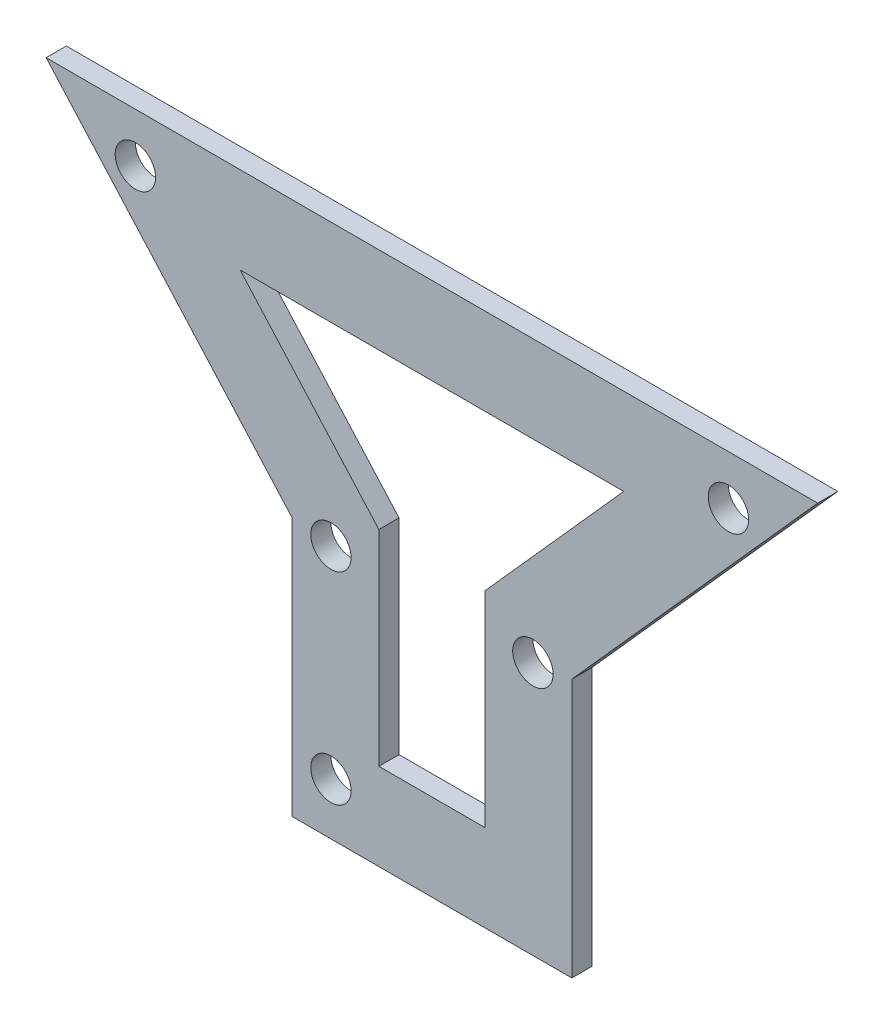
SolidWorks part; units mm, degrees
ref_plane "Спереди" through (0, 0, 0) normal (0, 0, 1) x (1, 0, 0)
ref_plane "Сверху" through (0, 0, 0) normal (0, 1, 0) x (1, 0, 0)
ref_plane "Справа" through (0, 0, 0) normal (1, 0, 0) x (0, 0, -1)
sketch "Эскиз5" plane through (0, 0, 0) normal (0, 0, 1) x (1, 0, 0)
  line L0 (0, -125.6018) -> (0, 84.5398) construction
  line L1 (69.2703, 2.5328) -> (69.2703, -125.6018)
  line L2 (69.2703, 2.5328) -> (190.9954, 138.8843)
  line L3 (190.9954, 138.8843) -> (-190.9954, 138.8843)
  line L4 (69.2703, -125.6018) -> (-69.2703, -125.6018)
  line L5 (-26.2703, -82.6018) -> (26.2703, -82.6018)
  line L6 (26.2703, -82.6018) -> (26.2703, 18.9341)
  line L7 (26.2703, 18.9341) -> (94.9661, 95.8843)
  line L8 (94.9661, 95.8843) -> (-94.9661, 95.8843)
  line L9 (-26.2703, 18.9341) -> (-94.9661, 95.8843)
  line L10 (-26.2703, -82.6018) -> (-26.2703, 18.9341)
  line L11 (-69.2703, 2.5328) -> (-190.9954, 138.8843)
  line L12 (-69.2703, 2.5328) -> (-69.2703, -125.6018)
  circle A0 centre (136.7614, 111.3834) radius 10 construction
  circle A1 centre (50, -10.9786) radius 10 construction
  circle A2 centre (50, -110.9786) radius 10 construction
  circle A3 centre (-50, -110.9786) radius 10 construction
  circle A4 centre (-50, -10.9786) radius 10 construction
  circle A5 centre (-136.7614, 111.3834) radius 10 construction
  point P33 (0, 95.8843)
  point P35 (0, -82.6018)
  point P37 (0, 138.8843)
  dimension "D1" = 20
  dimension "D5" = 43
  dimension "D2" = 50
  dimension "D3" = 100
  dimension "D4" = 150
  dimension "D6" = 43
  dimension "D7" = 43
  dimension "D8" = 43
extrude "Бобышка-Вытянуть2" add sketch "Эскиз5" along normal blind 10 contours L4 L12 L11 L3 L2 L1 | L8 L9 L10 L5 L6 L7
sketch "Эскиз6" plane through (0, 0, 10) normal (0, 0, 1) x (1, 0, 0)
  line L0 (0, 0) -> (0, 70.7406) construction
  circle A0 centre (-146.8076, 114.5787) radius 10
  circle A1 centre (146.8076, 114.5787) radius 10
  circle A2 centre (-50, 0) radius 10
  circle A3 centre (-50, -100) radius 10
  circle A4 centre (50, 0) radius 10
  point P13 (0, 0)
  point P14 (-49.1923, 0)
  point P15 (0, 0)
  point P16 (0, 0)
  point P17 (0, 0)
  point P18 (0, 0)
  point P19 (0, 0)
  point P20 (0, 0)
  dimension "D1" = 20
  dimension "D2" = 150
  dimension "D3" = 150
  dimension "D4" = 50
  dimension "D5" = 100
  dimension "D6" = 100
extrude "Вырез-Вытянуть2" cut sketch "Эскиз6" against normal blind 10
